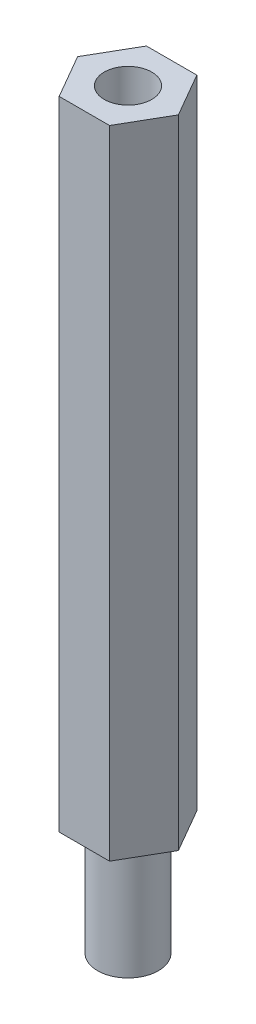
SolidWorks part; units mm, degrees
ref_plane "前视基准面" through (0, 0, 0) normal (0, 0, 1) x (1, 0, 0)
ref_plane "上视基准面" through (0, 0, 0) normal (0, 1, 0) x (1, 0, 0)
ref_plane "右视基准面" through (0, 0, 0) normal (1, 0, 0) x (0, 0, -1)
sketch "草图4" plane through (0, 0, 0) normal (0, 1, 0) x (1, 0, 0)
  line L0 (-12.7945, 0) -> (16.3015, 0) construction
  line L2 (1.325, -2.295) -> (2.65, 0)
  line L3 (2.65, 0) -> (1.325, 2.295)
  line L4 (1.325, 2.295) -> (-1.325, 2.295)
  line L5 (-1.325, 2.295) -> (-2.65, 0)
  line L6 (-2.65, 0) -> (-1.325, -2.295)
  line L7 (-1.325, -2.295) -> (1.325, -2.295)
  circle A0 centre (0, 0) radius 2.295 construction
  dimension "D1" = 5.3
extrude "凸台-拉伸1" add sketch "草图4" along normal blind 33.5
sketch "草图6" plane through (0, 0, 0) normal (0, -1, 0) x (-1, 0, 0)
  circle A0 centre (0, 0) radius 1.6
  dimension "D1" = 3.2
extrude "凸台-拉伸2" add sketch "草图6" along normal blind 6
cosmetic thread "装饰螺纹线1" parameters "D2"=2.5
sketch "草图7" plane through (0, 33.5, 0) normal (0, 1, 0) x (1, 0, 0)
  circle A0 centre (0, 0) radius 1.25
  dimension "D1" = 2.5
extrude "切除-拉伸1" cut sketch "草图7" against normal blind 5
cosmetic thread "装饰螺纹线2" parameters "D2"=3
